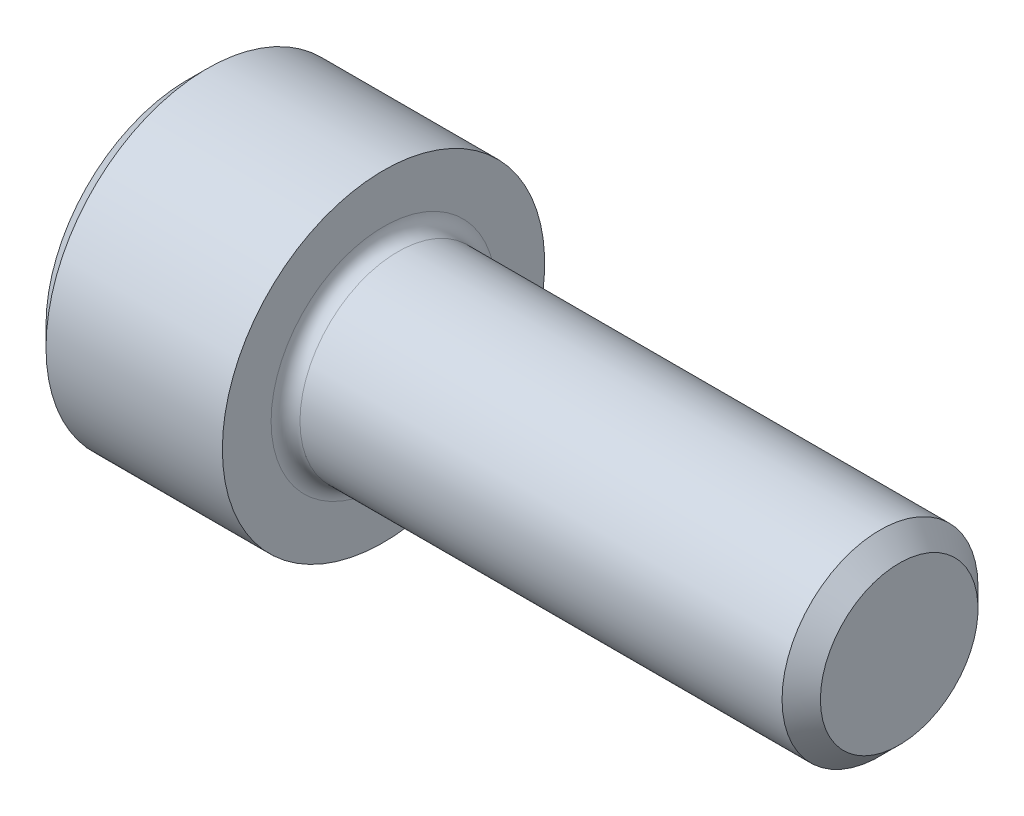
SolidWorks part; units mm, degrees
ref_plane "Plane1"
ref_plane "Plane2" through (0, 0, 0) normal (0, 1, 0) x (1, 0, 0)
ref_plane "Plane3" through (0, 0, 0) normal (1, 0, 0) x (0, 0, -1)
sketch "BodySke" plane through (0, 0, 0) normal (0, 0, 1) x (1, 0, 0)
  line L0 (0, 0) -> (0, 3.4861)
  line L1 (0.4826, 3.9688) -> (4.826, 3.9688)
  line L2 (4.826, 3.9688) -> (4.826, 2.413)
  line L3 (4.826, 2.413) -> (17.0536, 2.413)
  line L4 (17.526, 1.9406) -> (17.526, 0)
  line L5 (17.526, 0) -> (0, 0)
  line L6 (-31.75, 0) -> (127, 0) construction
  line L7 (0, 3.4861) -> (0.4826, 3.9688)
  line L8 (17.526, 1.9406) -> (17.0536, 2.413)
  line L9 (0, -3.4861) -> (0.4826, -3.9688) construction
  line L10 (17.526, -1.9406) -> (17.0536, -2.413) construction
  line L11 (5.6185, 9.525) -> (5.6185, 3.175) construction
  line L12 (4.826, 9.525) -> (4.826, 3.175) construction
  line L13 (-20.574, 9.525) -> (-20.574, 3.175) construction
  dimension "Diameter" = 4.826
  dimension "Head_ht" = 4.826
  dimension "Length" = 12.7
  dimension "Body_ch_ang" = 45
  dimension "Head_dia" = 7.9375
  dimension "Head_ch_ang" = 45
  dimension "Head_side_ht" = 4.3434
  dimension "Minor_dia" = 3.8811
  dimension "Advance" = 0.7925
  dimension "Thread_nom" = 12.7
  dimension "Thread_length" = 38.1
revolve "Base-Revolve" add sketch "BodySke"
cosmetic thread "ThreadCosmetic"
fillet "Fillet1" radius 0.3556 1 edges at (4.826, 0, 2.413)
sketch "Sketch2" plane through (0, 0, 0) normal (0, 0, 1) x (1, 0, 0)
  line L0 (0, 1.985) -> (2.286, 1.985)
  line L1 (2.286, 1.985) -> (3.432, 0)
  line L2 (-31.75, 0) -> (127, 0) construction
  line L3 (3.432, 0) -> (0, 0)
  line L4 (0, 0) -> (0, 1.985)
  line L5 (0, 3.4861) -> (0, -3.4861) construction
  line L6 (0, 0) -> (47.625, 0) construction
  line L7 (4.826, -3.9688) -> (4.826, 3.9688) construction
  dimension "D1" = 1.985
  dimension "D2" = 60
  dimension "Wall_thickness" = 2.54
revolve "Hex-PreBroach" cut sketch "Sketch2" angle 360 about L6
sketch "Sketch3" plane through (0, 0, 0) normal (-1, 0, 0) x (0, 0.5, 0.866)
  line L0 (1.146, 1.985) -> (-1.146, 1.985)
  line L1 (-1.146, 1.985) -> (-2.2921, 0)
  line L2 (1.146, 1.985) -> (2.2921, 0)
  line L3 (1.146, -1.985) -> (2.2921, 0)
  line L4 (1.146, -1.985) -> (-1.146, -1.985)
  line L5 (-1.146, -1.985) -> (-2.2921, 0)
  dimension "D1" = 1.985
  dimension "D2" = 1.985
  dimension "Hex_size" = 3.97
extrude "Hex" cut sketch "Sketch3" against normal blind 2.286
sketch "Sketch4" plane through (0, 0, 0) normal (-1, 0, 0) x (0, 0, 1)
  line L0 (0, 0) -> (2.3876, 0)
  line L1 (0, 0) -> (6.1484, 3.5498) construction
  line L2 (0, 0) -> (1.1938, 2.0677)
  line L3 (1.9883, 0.576) -> (2.2704, 0.7389)
  line L4 (1.493, 1.4339) -> (1.7751, 1.5968)
  arc A0 (1.9883, 0.576) -> (1.493, 1.4339) centre (0, 0) ccw
  arc A1 (2.3876, 0) -> (2.2704, 0.7389) centre (0, 0) ccw
  arc A2 (1.1938, 2.0677) -> (1.7751, 1.5968) centre (0, 0) cw
  dimension "D1" = 30
  dimension "Spline_n_dim" = 4.1402
  dimension "Spline_m_dim" = 4.7752
  dimension "D2" = 60
  dimension "D3" = 0.4953
  dimension "Spline_p_dim" = 0.9906
extrude "Spline" [suppressed] cut sketch "Sketch4" against normal blind 2.286
pattern_circular "CirPattern1" [suppressed] count 6 every 60
sketch "Sketch5" plane through (0, 0, 0) normal (0, 0, 1) x (1, 0, 0)
  line L0 (-31.75, 0) -> (127, 0) construction
  line L2 (0, 3.4861) -> (0, -3.4861) construction
  circle A0 centre (1.651, 0) radius 0.5905
  dimension "Drilled_hole_dia" = 1.1811
  dimension "Drilled_hole_loc" = 1.651
extrude "Hole" [suppressed] cut sketch "Sketch5" against normal through all and the other way through all
pattern_circular "Drilled-4" [suppressed] count 2 every 60
pattern_circular "Drilled-6" [suppressed] count 3 every 60
sketch "ThdSchSke" plane through (0, 0, 0) normal (0, 0, 1) x (1, 0, 0)
  line L0 (5.6185, -1.9406) -> (5.2877, -2.413)
  line L1 (5.6185, -1.9406) -> (5.9493, -2.413)
  line L2 (5.9493, -2.413) -> (5.9493, -3.0163)
  line L3 (-3.175, 0) -> (5.1513, 0) construction
  line L5 (5.9493, -3.0163) -> (5.2877, -3.0163)
  line L6 (5.2877, -3.0163) -> (5.2877, -2.413)
  line L7 (0, 3.4861) -> (0, -3.4861) construction
  dimension "Thread_minor" = 3.8811
  dimension "Diameter" = 4.826
  dimension "Start" = 5.6185
  dimension "SideAngle" = 55
  dimension "VeeAngle" = 70
  dimension "Overcut" = 6.0325
revolve "ThreadSchematic" [suppressed] cut sketch "ThdSchSke" angle 360 about L3
pattern_linear "ThdSchPat" [suppressed]
equation "\"D2@Sketch3\" = \"Hex_size@Sketch3\" / 2"
equation "\"D1@Sketch3\" = \"Hex_size@Sketch3\" / 2"
equation "\"D1@Sketch2\" = \"Hex_size@Sketch3\" / 2"
equation "\"D3@Sketch4\" = \"Spline_p_dim@Sketch4\" / 2"
equation "\"Thread_minor@ThreadCosmetic\"  =  \"Minor_dia@BodySke\""
equation "\"D2@CirPattern1\" = 360 / \"Num_teeth@CirPattern1\""
equation "\"Wall_thickness@Sketch2\" = \"Head_ht@BodySke\" - \"Key_eng@Hex\""
equation "\"Thread_length@ThreadCosmetic\" = ((sgn( (\"Length@BodySke\" - \"Advance@BodySke\" ) - \"Thread_nom@BodySke\" )-1)*( (\"Length@BodySke\" - \"Advance@BodySke\" ) - \"Thread_nom@BodySke\" ))/-2+ \"Thread_nom@BodySke\""
equation "\"Thread_minor@ThdSchSke\" = \"Minor_dia@BodySke\""
equation "\"Diameter@ThdSchSke\" = \"Diameter@BodySke\""
equation "\"Overcut@ThdSchSke\" = \"Diameter@BodySke\" * 1.25"
equation "\"Start@ThdSchSke\" = \"Head_ht@BodySke\" + \"Length@BodySke\" - \"Thread_length@ThreadCosmetic\"  '---Non-countersunk---"
equation "\"Num_threads@ThdSchPat\" = int( \"Thread_length@ThreadCosmetic\" / \"Advance@BodySke\" + 0.999 )  + 1"
equation "\"Advance@ThdSchPat\" = \"Thread_length@ThreadCosmetic\" /  (\"Num_threads@ThdSchPat\" - 1) 'relax it"
equation "\"Num_threads@ThdSchPat\" = \"Num_threads@ThdSchPat\" - sgn( \"Num_threads@ThdSchPat\" - 1) '---chamfered tips only---"
